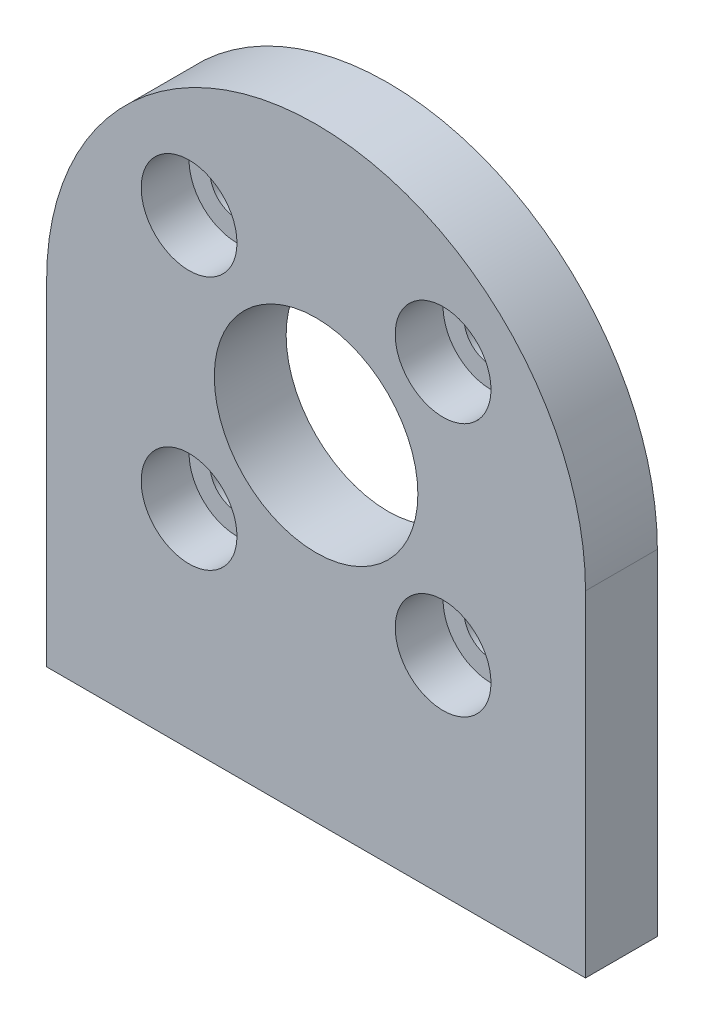
SolidWorks part; units mm, degrees
material "Сплав 2024"
ref_plane "Спереди" through (0, 0, 0) normal (0, 0, 1) x (1, 0, 0)
ref_plane "Сверху" through (0, 0, 0) normal (0, 1, 0) x (1, 0, 0)
ref_plane "Справа" through (0, 0, 0) normal (1, 0, 0) x (0, 0, -1)
sketch "Эскиз1" plane through (0, 0, 0) normal (0, 0, 1) x (1, 0, 0)
  line L0 (22.5, 0) -> (22.5, 62.6444) construction
  line L2 (0, 28) -> (0, 0)
  line L3 (0, 0) -> (45, 0)
  line L4 (45, 28) -> (45, 0)
  arc A1 (45, 28) -> (0, 28) centre (22.5, 28) ccw
  point P0 (0, 25)
  point P4 (20.0824, 6.1398)
  point P12 (24, 0)
  dimension "D1" = 22.5
  dimension "D4" = 45
  dimension "D2" = 28
extrude "Бобышка-Вытянуть1" add sketch "Эскиз1" along normal blind 6
sketch "Эскиз2" plane through (0, 0, 6) normal (0, 0, 1) x (1, 0, 0)
  circle A0 centre (22.5, 28) radius 8.5
  dimension "D1" = 17
extrude "Вырез-Вытянуть1" cut sketch "Эскиз2" against normal through all
sketch "Эскиз3" plane through (0, 0, 6) normal (0, 0, 1) x (1, 0, 0)
  line L0 (22.5, 28) -> (46.7565, 28) construction
  line L1 (41.8287, 47.3287) -> (1.7543, 7.2543) construction
  line L2 (1.0263, 49.4737) -> (43.373, 7.127) construction
  circle A0 centre (22.5, 28) radius 15 construction
  dimension "D1" = 30
  dimension "D2" = 45
hole_wizard "Цековка для винта с внутренним шестигранником M41" positions "Эскиз5" profile "Эскиз4" counterbore size "M4" standard "Ansi Metric" end condition through all
sketch "Эскиз5" plane through (0, 0, 6) normal (0, 0, 1) x (1, 0, 0)
  line L0 (1.0263, 49.4737) -> (43.373, 7.127) construction
  line L1 (41.8287, 47.3287) -> (1.7543, 7.2543) construction
  circle A0 centre (22.5, 28) radius 15 construction
  point P0 (11.8934, 38.6066)
  point P6 (33.1066, 38.6066)
  point P10 (33.1066, 17.3934)
  point P12 (11.8934, 17.3934)
sketch "Эскиз4" plane through (11.8934, 38.6066, 6) normal (1, 0, 0) x (0, -1, 0)
  line L0 (0, 0) -> (0, 6)
  line L1 (0, 6) -> (2.25, 6)
  line L3 (2.25, 6) -> (2.25, 4)
  line L4 (2.25, 4) -> (4, 4)
  line L5 (4, 4) -> (4, 0)
  line L7 (4, 0) -> (0, 0)
  line L11 (0, -6.35) -> (0, 107.95) construction
  dimension "Диаметр сквозного отверстия" = 4.5
  dimension "Глубина сквозного отверстия" = 6
  dimension "Диаметр цековки" = 8
  dimension "Глубина цековки" = 4
